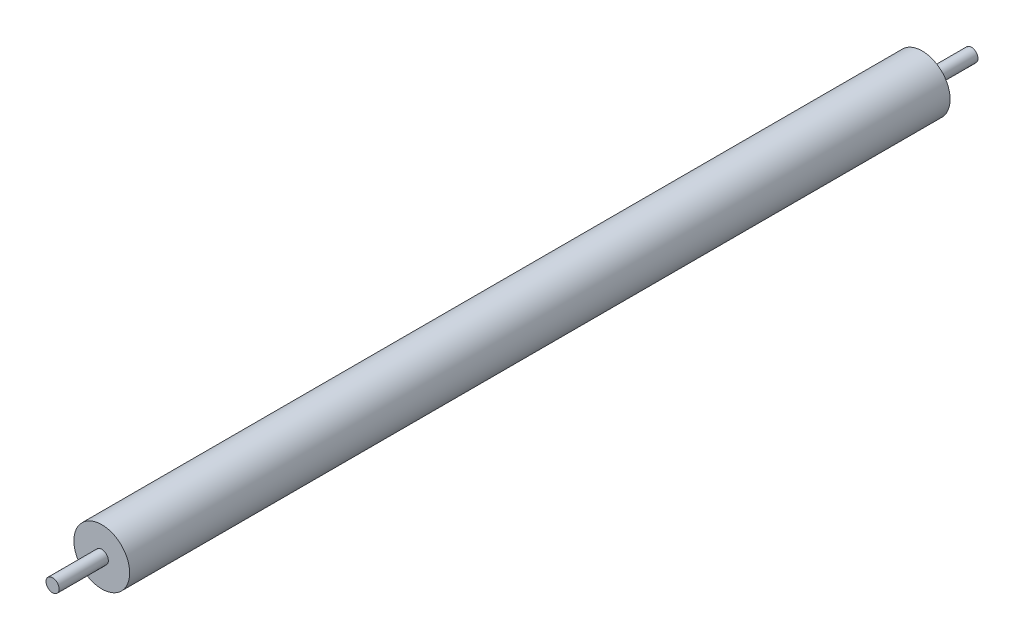
SolidWorks part; units mm, degrees
ref_plane "Front Plane" through (0, 0, 0) normal (0, 0, 1) x (1, 0, 0)
ref_plane "Top Plane" through (0, 0, 0) normal (0, 1, 0) x (1, 0, 0)
ref_plane "Right Plane" through (0, 0, 0) normal (1, 0, 0) x (0, 0, -1)
sketch "Sketch1" plane through (0, 0, 0) normal (0, 0, 1) x (1, 0, 0)
  circle A0 centre (0, 0) radius 4
  dimension "D1" = 8
extrude "Boss-Extrude1" add sketch "Sketch1" along normal blind 560
ref_plane "Plane1" through (0, 0, 280) normal (0, 0, 1) x (1, 0, 0)
sketch "Sketch2" plane through (0, 0, 280) normal (0, 0, 1) x (1, 0, 0)
  circle A0 centre (0, 0) radius 17
  dimension "D1" = 34
extrude "Boss-Extrude2" add sketch "Sketch2" along normal mid plane 500
